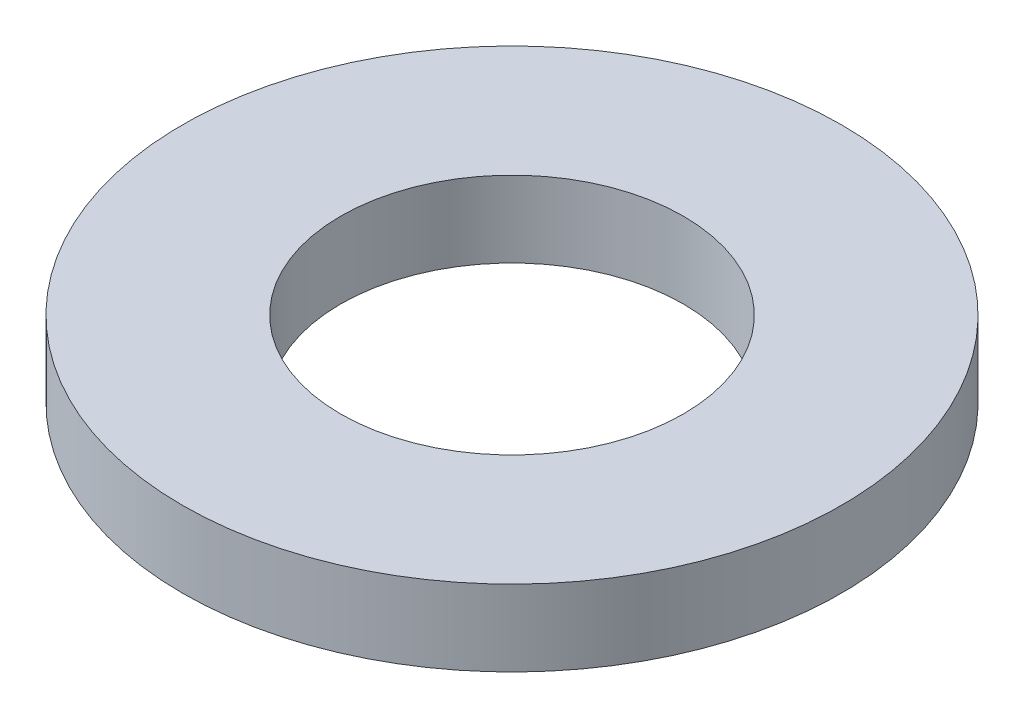
SolidWorks part; units mm, degrees
ref_plane "Alzado" through (0, 0, 0) normal (0, 0, 1) x (1, 0, 0)
ref_plane "Planta" through (0, 0, 0) normal (0, 1, 0) x (1, 0, 0)
ref_plane "Vista lateral" through (0, 0, 0) normal (1, 0, 0) x (0, 0, -1)
sketch "Sketch1" plane through (0, 0, 0) normal (0, 1, 0) x (1, 0, 0)
  circle A0 centre (0, 0) radius 14.3
  circle A1 centre (0, 0) radius 27.5
  dimension "D1" = 28.6
  dimension "D2" = 55
extrude "Boss-Extrude1" add sketch "Sketch1" along normal blind 6.35
